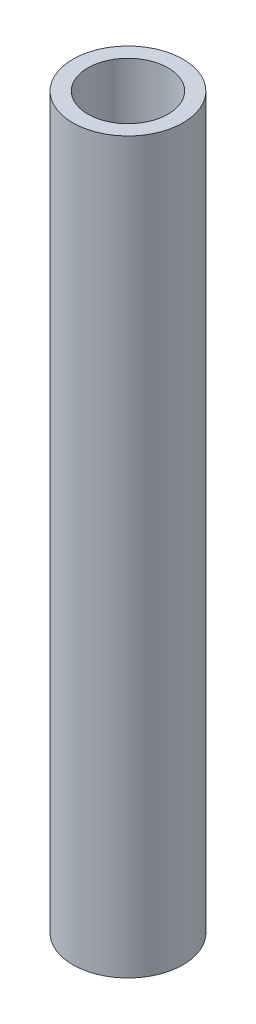
SolidWorks part; units mm, degrees
ref_plane "Front Plane" through (0, 0, 0) normal (0, 0, 1) x (1, 0, 0)
ref_plane "Top Plane" through (0, 0, 0) normal (0, 1, 0) x (1, 0, 0)
ref_plane "Right Plane" through (0, 0, 0) normal (1, 0, 0) x (0, 0, -1)
sketch "Sketch1" plane through (0, 0, 0) normal (0, 1, 0) x (1, 0, 0)
  circle A0 centre (0, 0) radius 12.1539
  circle A1 centre (0, 0) radius 16.7005
  dimension "D1" = 24.3078
  dimension "D2" = 33.401
extrude "Boss-Extrude1" add sketch "Sketch1" along normal mid plane 220.98
